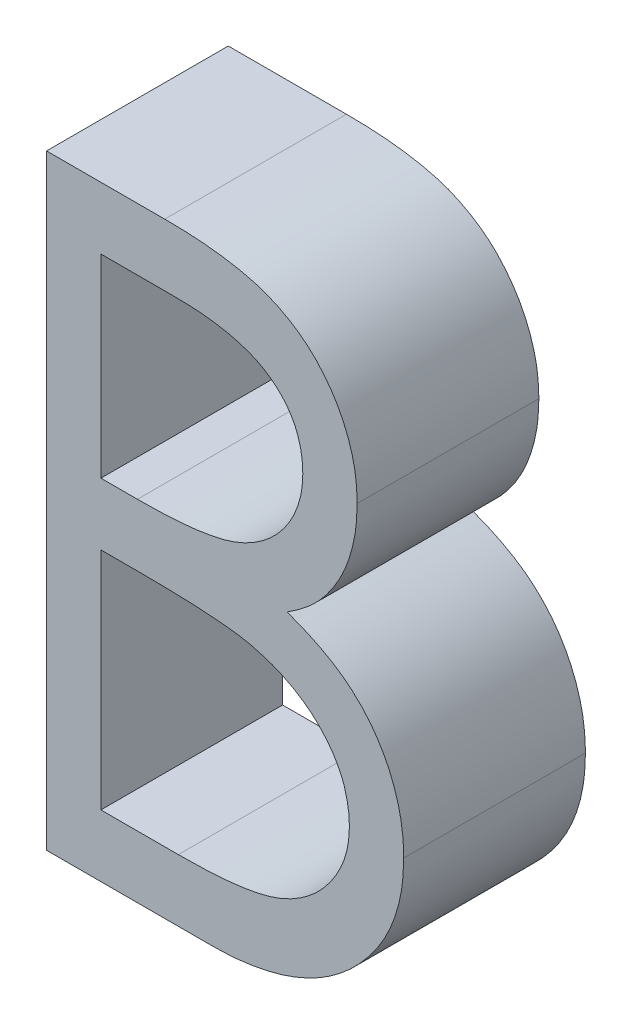
SolidWorks part; units mm, degrees
ref_plane "Plan de face" through (0, 0, 0) normal (0, 0, 1) x (1, 0, 0)
ref_plane "Plan de dessus" through (0, 0, 0) normal (0, 1, 0) x (1, 0, 0)
ref_plane "Plan de droite" through (0, 0, 0) normal (1, 0, 0) x (0, 0, -1)
sketch "Esquisse1" plane through (0, 0, 0) normal (0, 0, 1) x (1, 0, 0)
  text T0 "B" font "Century Gothic" height 5
extrude "Boss.-Extru.1" add sketch "Esquisse1" along normal blind 1.5
